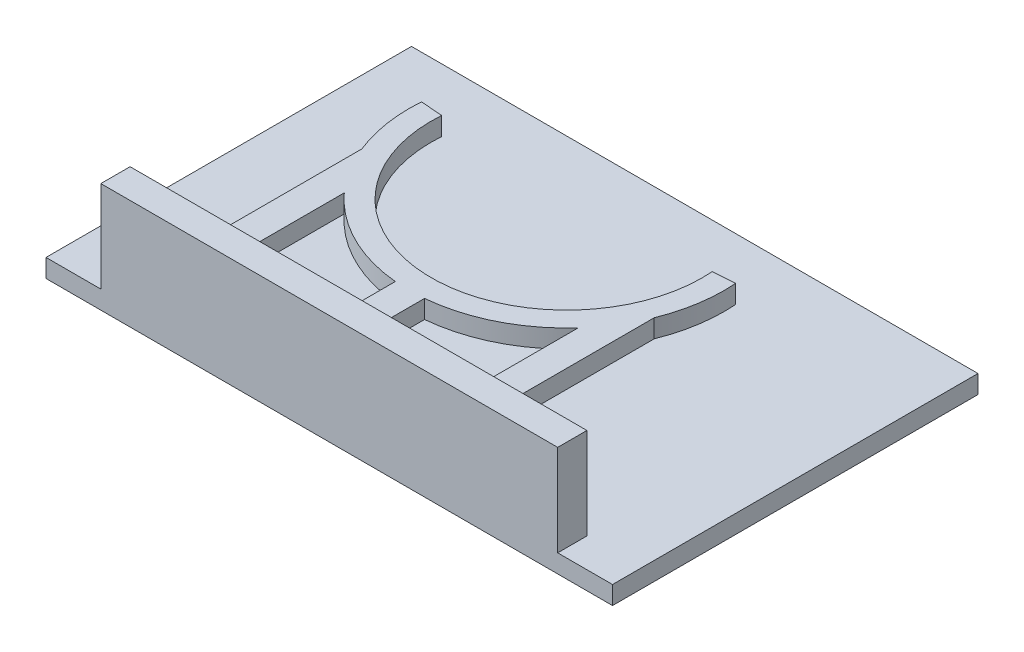
SolidWorks part; units mm, degrees
ref_plane "前视基准面" through (0, 0, 0) normal (0, 0, 1) x (1, 0, 0)
ref_plane "上视基准面" through (0, 0, 0) normal (0, 1, 0) x (1, 0, 0)
ref_plane "右视基准面" through (0, 0, 0) normal (1, 0, 0) x (0, 0, -1)
sketch "草图1" plane through (0, 0, 0) normal (0, 1, 0) x (1, 0, 0)
  line L1 (0, 0) -> (155, 0)
  line L2 (0, 0) -> (0, 100)
  line L3 (0, 100) -> (155, 100)
  line L4 (155, 0) -> (155, 100)
  dimension "D1" = 155
  dimension "D2" = 100
extrude "凸台-拉伸1" add sketch "草图1" along normal blind 5
sketch "草图2" plane through (0, 5, 0) normal (0, 1, 0) x (1, 0, 0)
  line L0 (0, 0) -> (155, 0) construction
  line L1 (15, 0) -> (140, 0)
  line L2 (15, 0) -> (15, 8)
  line L3 (15, 8) -> (140, 8)
  line L4 (140, 0) -> (140, 8)
  line L5 (0, 100) -> (0, 0) construction
  line L6 (155, 0) -> (155, 100) construction
  dimension "D1" = 15
  dimension "D2" = 15
  dimension "D3" = 8
extrude "凸台-拉伸2" add sketch "草图2" along normal blind 25
sketch "草图3" plane through (0, 0, -8) normal (0, 0, -1) x (-1, 0, 0)
  line L0 (-77.5, 30) -> (-77.5, 5) construction
  line L1 (-140, 5) -> (-15, 5) construction
  line L3 (-62, 30) -> (-62, 5) construction
  line L4 (-50.5, 30) -> (-50.5, 5) construction
  line L5 (-39.5, 30) -> (-39.5, 5) construction
  line L6 (-37.5, 30) -> (-37.5, 5) construction
  point P4 (-77.5, 5)
  point P5 (-50.5, 5)
  point P13 (-62, 5)
  point P15 (-50.5, 5)
  point P16 (-39.5, 5)
  point P17 (-37.5, 5)
  dimension "D1" = 15.5
  dimension "D2" = 27
  dimension "D3" = 38
  dimension "D4" = 40
sketch3d "3D草图2"
  line L0 (77.5, 30, -8) -> (77.5, 5, -8) construction
  line L1 (62, 30, -8) -> (62, 5, -8) construction
  line L2 (50.5, 30, -8) -> (50.5, 5, -8) construction
  line L3 (39.5, 30, -8) -> (39.5, 5, -8) construction
  line L4 (37.5, 30, -8) -> (37.5, 5, -8) construction
sketch "草图4" plane through (0, 0, -8) normal (0, 0, -1) x (-1, 0, 0)
  line L0 (-140, 25) -> (-15, 25) construction
  line L3 (-140, 5) -> (-15, 5) construction
  dimension "D1" = 20
sketch3d "3D草图3" plane through (0, 0, 0) normal (0, 0, 1) x (1, 0, 0)
sketch "草图5" plane through (0, 5, 0) normal (0, 1, 0) x (1, 0, 0)
  line L0 (77.5, 100) -> (77.5, 0) construction
  line L1 (155, 100) -> (0, 100) construction
  line L2 (15, 0) -> (140, 0) construction
sketch "草图6" plane through (0, 5, 0) normal (0, 1, 0) x (1, 0, 0)
  line L0 (37.5, 8) -> (37.5, 50008) construction
  line L1 (140, 8) -> (15, 8) construction
  line L2 (39.5, 8) -> (39.5, 50008) construction
  line L3 (50.5, 8) -> (50.5, 50008) construction
  line L4 (62, 8) -> (62, 50008) construction
  line L5 (77.5, -3.6088) -> (77.5, 49996.3912) construction
  line L6 (-962.5, 65) -> (49037.5, 65) construction
  point P16 (77.5, 25)
  point P17 (37.5, 65)
  point P18 (117.5, 65)
  dimension "D1" = 40
  dimension "D2" = 40
  dimension "D3" = 40
  dimension "D4" = 17
sketch "草图7" plane through (0, 5, 0) normal (0, 1, 0) x (1, 0, 0)
  line L0 (37.5, -199992) -> (37.5, 250008) construction
  line L1 (34.5084, 68.2244) -> (40.4916, 67.7756)
  line L2 (114.5084, 67.7756) -> (120.4916, 68.2244)
  arc A0 (37.5, 65) -> (117.5, 65) centre (77.5, 65) ccw construction
  arc A3 (37.5, 68) -> (117.5, 68) centre (77.5, 65) ccw construction
  arc A4 (34.5084, 68.2244) -> (120.4916, 68.2244) centre (77.5, 65) ccw
  arc A5 (40.4916, 67.7756) -> (114.5084, 67.7756) centre (77.5, 65) ccw
  dimension "D1" = 3
  dimension "D3" = 3
  dimension "D2" = 3
  dimension "D4" = 3
extrude "凸台-拉伸6" add sketch "草图7" along normal blind 20
sketch "草图11" plane through (0, 0, -8) normal (0, 0, -1) x (-1, 0, 0)
  line L0 (-81.5, 25) -> (-73.5, 25)
  line L1 (-81.5, 25) -> (-81.5, 20)
  line L2 (-73.5, 25) -> (-73.5, 20)
  line L3 (-81.5, 20) -> (-73.5, 20)
  line L4 (-140, 25) -> (-15, 25) construction
  line L5 (-77.5, 200030) -> (-77.5, -199995) construction
  line L6 (-37.5, 200030) -> (-37.5, -199995) construction
  line L7 (-37.5, 25) -> (-45.5, 25)
  line L8 (-37.5, 25) -> (-37.5, 20)
  line L9 (-37.5, 20) -> (-45.5, 20)
  line L10 (-45.5, 25) -> (-45.5, 20)
  line L12 (-117.5, 25) -> (-109.5, 25)
  line L13 (-117.5, 25) -> (-117.5, 20)
  line L14 (-117.5, 20) -> (-109.5, 20)
  line L15 (-109.5, 25) -> (-109.5, 20)
  dimension "D1" = 4
  dimension "D2" = 4
  dimension "D3" = 5
  dimension "D4" = 8
  dimension "D5" = 8
  dimension "D6" = 28
  dimension "D7" = 28
extrude "凸台-拉伸7" add sketch "草图11" along normal up to next
sketch "草图12" plane through (0, 0, -8) normal (0, 0, -1) x (-1, 0, 0)
  line L0 (-140, 30) -> (-140, 5) construction
  line L1 (-140, 20) -> (-15, 20)
  line L2 (-140, 20) -> (-140, 5)
  line L3 (-140, 5) -> (-15, 5)
  line L4 (-15, 20) -> (-15, 5)
  line L5 (-15, 30) -> (-15, 5) construction
  line L6 (-140, 30) -> (-15, 30) construction
  dimension "D1" = 10
  dimension "D2" = 15
extrude "切除-拉伸1" cut sketch "草图12" along normal blind 130 contours L1 L4 L3 L2
sketch3d "3D草图4" plane through (0, 0, 0) normal (0, 0, 1) x (1, 0, 0)
  dimension "D1" = 2
sketch "草图16" plane through (0, 18, 0) normal (0, -1, 0) x (-1, 0, 0)
  line L0 (-74.5, 25) -> (-80.5, 25) construction
  line L1 (-80.5, 25) -> (-74.5, 25)
  arc A2 (-74.5, 25) -> (-80.5, 25) centre (-77.5, 25) cw
revolve "切除-旋转3" cut sketch "草图16" angle 360 about L0
pattern_circular "阵列(圆周)1" count 5 over 90 about axis through (77.5, 0, -65) along (0, 1, 0) of "切除-旋转3"
